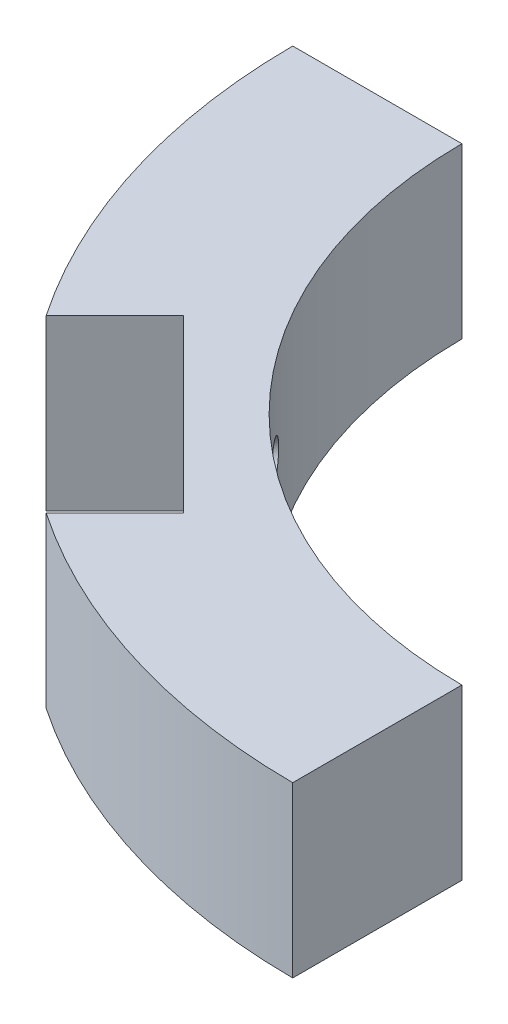
SolidWorks part; units mm, degrees
material "6061-T6 (SS)"
ref_plane "Front Plane" through (0, 0, 0) normal (0, 0, 1) x (1, 0, 0)
ref_plane "Top Plane" through (0, 0, 0) normal (0, 1, 0) x (1, 0, 0)
ref_plane "Right Plane" through (0, 0, 0) normal (1, 0, 0) x (0, 0, -1)
sketch "Sketch1" plane through (0, 0, 0) normal (0, 1, 0) x (1, 0, 0)
  line L0 (0, 0) -> (-24.5, 0) construction
  line L1 (0, 0) -> (0, -24.5) construction
  line L2 (-19.4997, -0.1) -> (-26.4998, -0.1)
  line L3 (-0.1, -19.4997) -> (-0.1, -26.4998)
  line L4 (-0.1, -0.1) -> (-24.5, -0.1) construction
  line L5 (-0.1, -0.1) -> (-0.1, -24.5) construction
  arc A0 (-19.4997, -0.1) -> (-0.1, -19.4997) centre (0, 0) ccw
  arc A1 (-26.4998, -0.1) -> (-0.1, -26.4998) centre (0, 0) ccw
  dimension "D1" = 39
  dimension "D2" = 53
  dimension "D3" = 0.1
extrude "Boss-Extrude1" add sketch "Sketch1" along normal mid plane 7
sketch "Sketch2" plane through (0, 3.5, 0) normal (0, 1, 0) x (1, 0, 0)
  line L0 (-18.7383, -18.7383) -> (0, 0) construction
  line L1 (-22.2739, -15.2028) -> (-15.2028, -22.2739)
  line L5 (-22.2739, -15.2028) -> (-19.0919, -12.0208)
  line L6 (-19.0919, -12.0208) -> (-12.0208, -19.0919)
  line L7 (-12.0208, -19.0919) -> (-15.2028, -22.2739)
  arc A0 (-26.4998, -0.1) -> (-0.1, -26.4998) centre (0, 0) ccw construction
  point P9 (-18.7383, -18.7383)
  dimension "D1" = 4.5
  dimension "D2" = 10
extrude "Cut-Extrude1" cut sketch "Sketch2" against normal through all
sketch "Sketch3" plane through (-15.5563, 0, 15.5563) normal (-0.7071, 0, 0.7071) x (0.7071, 0, 0.7071)
  line L0 (-5, 0) -> (5, 0) construction
  line L1 (-5, -3.5) -> (-5, 3.5) construction
  line L2 (5, 3.5) -> (5, -3.5) construction
  line L3 (0, 0) -> (0, 3.5) construction
  line L4 (5, 3.5) -> (-5, 3.5) construction
  point P6 (-2.5, 0)
  point P12 (2.5, 0)
  dimension "D1" = 2.5
hole_wizard "Tap Drill for M2x0.4 Tap1" positions "3DSketch1" profile "Sketch4" hole size "M2x0.4" standard "ANSI Metric" end condition through all
sketch3d "3DSketch1"
  point P0 (-17.3241, 0, 13.7886)
  point P3 (-13.7886, 0, 17.3241)
sketch "Sketch4" plane through (-17.3241, 0, 13.7886) normal (0, 1, 0) x (0.7071, 0, 0.7071)
  line L0 (0, 0) -> (0, 21.8586)
  line L1 (0, 21.8586) -> (0.8, 21.8586)
  line L2 (0.8, 21.8586) -> (0.8, 0)
  line L5 (0.8, 0) -> (0, 0)
  line L11 (0, -6.35) -> (0, 107.95) construction
  dimension "Thru Hole Dia." = 1.6
  dimension "Thru Hole Depth" = 21.8586
